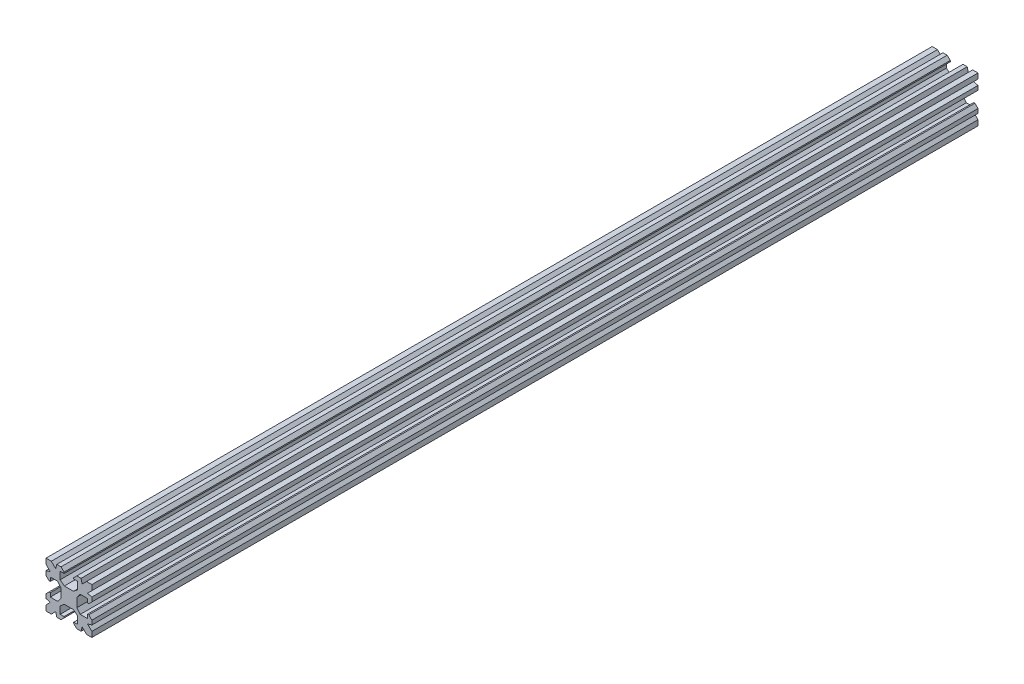
SolidWorks part; units mm, degrees
ref_plane "Спереди" through (0, 0, 0) normal (0, 0, 1) x (1, 0, 0)
ref_plane "Сверху" through (0, 0, 0) normal (0, 1, 0) x (1, 0, 0)
ref_plane "Справа" through (0, 0, 0) normal (1, 0, 0) x (0, 0, -1)
sketch "Эскиз1" plane through (0, 0, 0) normal (0, 0, 1) x (1, 0, 0)
  line L0 (1.58, 6.1) -> (2.85, 6.1)
  line L1 (-7.5, -7.5) -> (7.5, -7.5)
  line L2 (-7.5, -7.5) -> (-7.5, 7.5)
  line L3 (-7.5, 7.5) -> (7.5, 7.5)
  line L4 (7.5, -7.5) -> (7.5, 7.5)
  line L5 (-2.85, 6.1) -> (-1.58, 6.1)
  line L6 (-2.85, 6.1) -> (-2.85, 3.7)
  line L7 (-2.85, 3.7) -> (2.85, 3.7)
  line L8 (2.85, 6.1) -> (2.85, 3.7)
  line L9 (-2.85, 6.1) -> (2.85, 3.7) construction
  line L10 (-2.85, 3.7) -> (2.85, 6.1) construction
  line L11 (-1.58, 7.5) -> (1.58, 7.5)
  line L12 (-1.58, 7.5) -> (-1.58, 6.1)
  line L14 (1.58, 7.5) -> (1.58, 6.1)
  line L15 (-1.58, 7.5) -> (1.58, 6.1) construction
  line L16 (-1.58, 6.1) -> (1.58, 7.5) construction
  line L17 (6.1, -1.58) -> (6.1, -2.85)
  line L18 (6.1, 2.85) -> (6.1, 1.58)
  line L19 (6.1, 2.85) -> (3.7, 2.85)
  line L20 (3.7, 2.85) -> (3.7, -2.85)
  line L21 (6.1, -2.85) -> (3.7, -2.85)
  line L22 (7.5, 1.58) -> (7.5, -1.58)
  line L23 (7.5, 1.58) -> (6.1, 1.58)
  line L24 (7.5, -1.58) -> (6.1, -1.58)
  line L25 (6.1, 2.85) -> (3.7, -2.85) construction
  line L26 (3.7, 2.85) -> (6.1, -2.85) construction
  line L27 (7.5, 1.58) -> (6.1, -1.58) construction
  line L28 (6.1, 1.58) -> (7.5, -1.58) construction
  line L29 (-1.58, -6.1) -> (-2.85, -6.1)
  line L30 (2.85, -6.1) -> (1.58, -6.1)
  line L31 (2.85, -6.1) -> (2.85, -3.7)
  line L32 (2.85, -3.7) -> (-2.85, -3.7)
  line L33 (-2.85, -6.1) -> (-2.85, -3.7)
  line L34 (1.58, -7.5) -> (-1.58, -7.5)
  line L35 (1.58, -7.5) -> (1.58, -6.1)
  line L36 (-1.58, -7.5) -> (-1.58, -6.1)
  line L37 (2.85, -6.1) -> (-2.85, -3.7) construction
  line L38 (2.85, -3.7) -> (-2.85, -6.1) construction
  line L39 (1.58, -7.5) -> (-1.58, -6.1) construction
  line L40 (1.58, -6.1) -> (-1.58, -7.5) construction
  line L41 (-6.1, 1.58) -> (-6.1, 2.85)
  line L42 (-6.1, -2.85) -> (-6.1, -1.58)
  line L43 (-6.1, -2.85) -> (-3.7, -2.85)
  line L44 (-3.7, -2.85) -> (-3.7, 2.85)
  line L45 (-6.1, 2.85) -> (-3.7, 2.85)
  line L46 (-7.5, -1.58) -> (-7.5, 1.58)
  line L47 (-7.5, -1.58) -> (-6.1, -1.58)
  line L48 (-7.5, 1.58) -> (-6.1, 1.58)
  line L49 (-6.1, -2.85) -> (-3.7, 2.85) construction
  line L50 (-3.7, -2.85) -> (-6.1, 2.85) construction
  line L51 (-7.5, -1.58) -> (-6.1, 1.58) construction
  line L52 (-6.1, -1.58) -> (-7.5, 1.58) construction
  line L53 (-5.762, 7.5) -> (-4.342, 6.08)
  line L54 (-4.342, 6.08) -> (-3.962, 7.5)
  line L55 (-3.962, 7.5) -> (-5.762, 7.5)
  line L56 (-7.5, 7.5) -> (0, 0) construction
  line L57 (-6.08, 4.342) -> (-7.5, 3.962)
  line L58 (-7.5, 5.762) -> (-6.08, 4.342)
  line L59 (-7.5, 3.962) -> (-7.5, 5.762)
  line L60 (4.342, 6.08) -> (3.962, 7.5)
  line L61 (3.962, 7.5) -> (5.762, 7.5)
  line L62 (5.762, 7.5) -> (4.342, 6.08)
  line L63 (7.5, 3.962) -> (7.5, 5.762)
  line L64 (7.5, 5.762) -> (6.08, 4.342)
  line L65 (6.08, 4.342) -> (7.5, 3.962)
  line L66 (6.08, -4.342) -> (7.5, -3.962)
  line L67 (7.5, -3.962) -> (7.5, -5.762)
  line L68 (7.5, -5.762) -> (6.08, -4.342)
  line L69 (3.962, -7.5) -> (5.762, -7.5)
  line L70 (5.762, -7.5) -> (4.342, -6.08)
  line L71 (4.342, -6.08) -> (3.962, -7.5)
  line L72 (-4.342, -6.08) -> (-3.962, -7.5)
  line L73 (-3.962, -7.5) -> (-5.762, -7.5)
  line L74 (-5.762, -7.5) -> (-4.342, -6.08)
  line L75 (-7.5, -3.962) -> (-7.5, -5.762)
  line L76 (-7.5, -5.762) -> (-6.08, -4.342)
  line L77 (-6.08, -4.342) -> (-7.5, -3.962)
  point P0 (0, 0)
  point P5 (0, 4.9)
  point P12 (7.5, 0)
  point P13 (0, -7.5)
  point P14 (0, 6.8)
  point P19 (4.9, 0)
  point P26 (6.8, 0)
  point P31 (0, -4.9)
  point P36 (0, -6.8)
  point P41 (-4.9, 0)
  point P46 (-6.8, 0)
  point P51 (0, 0)
  point P77 (0, 0)
  dimension "D1" = 15
  dimension "D2" = 3.16
  dimension "D3" = 5.7
  dimension "D4" = 1.4
  dimension "D5" = 4
  dimension "D6" = 7.4
  dimension "D7" = 1.8
  dimension "D8" = 1.42
  dimension "D9" = 4
extrude "Бобышка-Вытянуть1" add sketch "Эскиз1" along normal blind 290 contours L77 L76 L2 L1 L74 L72 L36 L29 L33 L32 L31 L30 L35 L71 L70 L4 L68 L66 L24 L17 L21 L20 L19 L18 L23 L65 L64 L3 L62 L60 L14 L0 L8 L7 L6 L5 L12 L54 L53 L58 L57
sketch "Эскиз2" plane through (0, 0, 290) normal (0, 0, 1) x (1, 0, 0)
  line L0 (-3.7, 2.85) -> (-2.6, 1.5)
  line L1 (-2.6, 1.5) -> (-2.6, -1.5)
  line L2 (-2.6, -1.5) -> (-3.7, -2.85)
  line L3 (-3.7, -2.85) -> (-3.7, 2.85)
  line L4 (-7.5, -3.962) -> (-7.5, -1.58) construction
  line L5 (2.85, 3.7) -> (1.5, 2.6)
  line L6 (1.5, 2.6) -> (-1.5, 2.6)
  line L7 (-1.5, 2.6) -> (-2.85, 3.7)
  line L8 (-2.85, 3.7) -> (2.85, 3.7)
  line L9 (3.7, -2.85) -> (2.6, -1.5)
  line L10 (2.6, -1.5) -> (2.6, 1.5)
  line L11 (2.6, 1.5) -> (3.7, 2.85)
  line L12 (3.7, 2.85) -> (3.7, -2.85)
  line L13 (-2.85, -3.7) -> (-1.5, -2.6)
  line L14 (-1.5, -2.6) -> (1.5, -2.6)
  line L15 (1.5, -2.6) -> (2.85, -3.7)
  line L16 (2.85, -3.7) -> (-2.85, -3.7)
  point P6 (-2.6, 0)
  point P19 (0, 2.6)
  point P24 (2.6, 0)
  point P29 (0, -2.6)
  point P30 (0, 0)
  dimension "D1" = 3
  dimension "D2" = 4.9
  dimension "D3" = 4
extrude "Вырез-Вытянуть1" cut sketch "Эскиз2" against normal through all
chamfer "Фаска1" distance 1 angle 45 8 edges at (-7.5, 1.58, 145) (-7.5, -1.58, 145) (1.58, -7.5, 145) (-1.58, -7.5, 145) (7.5, -1.58, 145) (7.5, 1.58, 145) (1.58, 7.5, 145) (-1.58, 7.5, 145)
